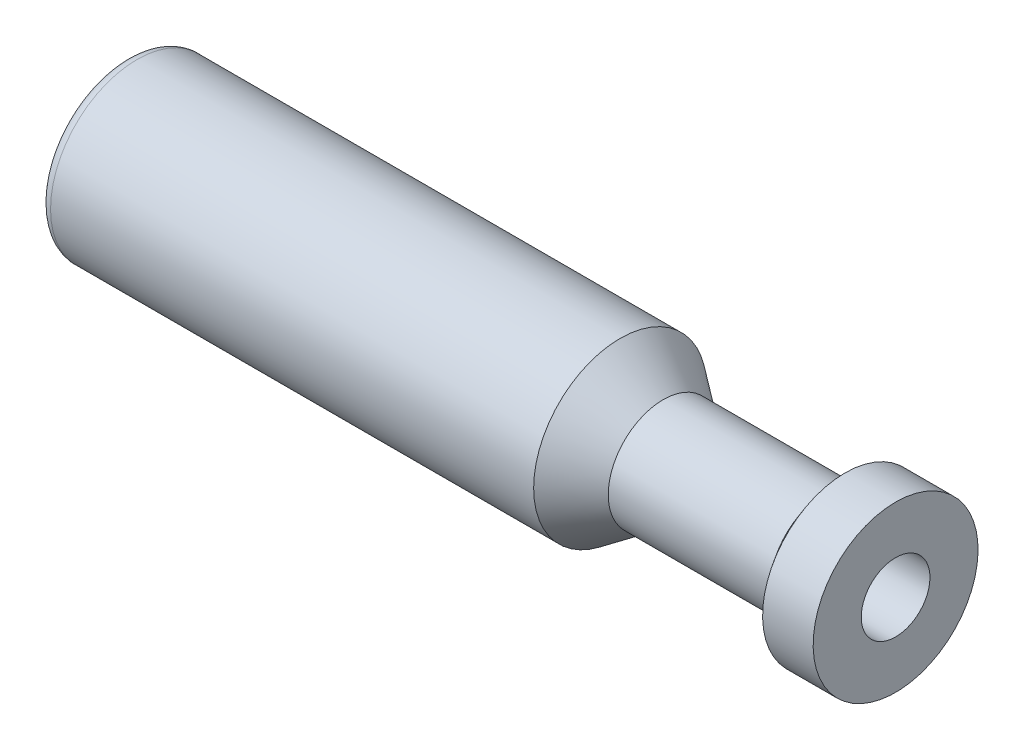
SolidWorks part; units mm, degrees
material "Natural Rubber"
ref_plane "Front Plane" through (0, 0, 0) normal (0, 0, 1) x (1, 0, 0)
ref_plane "Top Plane" through (0, 0, 0) normal (0, 1, 0) x (1, 0, 0)
ref_plane "Right Plane" through (0, 0, 0) normal (1, 0, 0) x (0, 0, -1)
sketch "Sketch1" plane through (0, 0, 0) normal (0, 0, 1) x (1, 0, 0)
  line L1 (107.503, -34.9609) -> (117.4522, -42.2436)
  line L2 (117.4522, -42.2436) -> (154.8187, -42.2436)
  line L3 (154.8187, -42.2436) -> (159.4668, -35.8936)
  line L4 (159.4668, -35.8936) -> (171.1455, -35.8936)
  line L5 (171.1455, -35.8936) -> (171.1455, -54.9436)
  line L6 (171.1455, -54.9436) -> (-31.8619, -54.9436) construction
  line L8 (-6.6545, -54.9436) -> (171.1455, -54.9436)
  line L9 (107.503, -34.9609) -> (-6.6545, -34.9609)
  line L10 (-6.6545, -34.9609) -> (-6.6545, -54.9436)
  dimension "D1" = 19.05
  dimension "D3" = 12.7
  dimension "D4" = 177.8
revolve "Revolve1" add sketch "Sketch1" angle 360 about L6
sketch "Sketch4" plane through (171.1455, 0, 0) normal (1, 0, 0) x (0, 0, -1)
  circle A0 centre (0, -54.9436) radius 7.9375
  dimension "D1" = 15.875
extrude "Cut-Extrude1" cut sketch "Sketch4" against normal blind 190.5
fillet "Fillet1" radius 2.54 1 edges at (-6.6545, -34.9609, 0)
